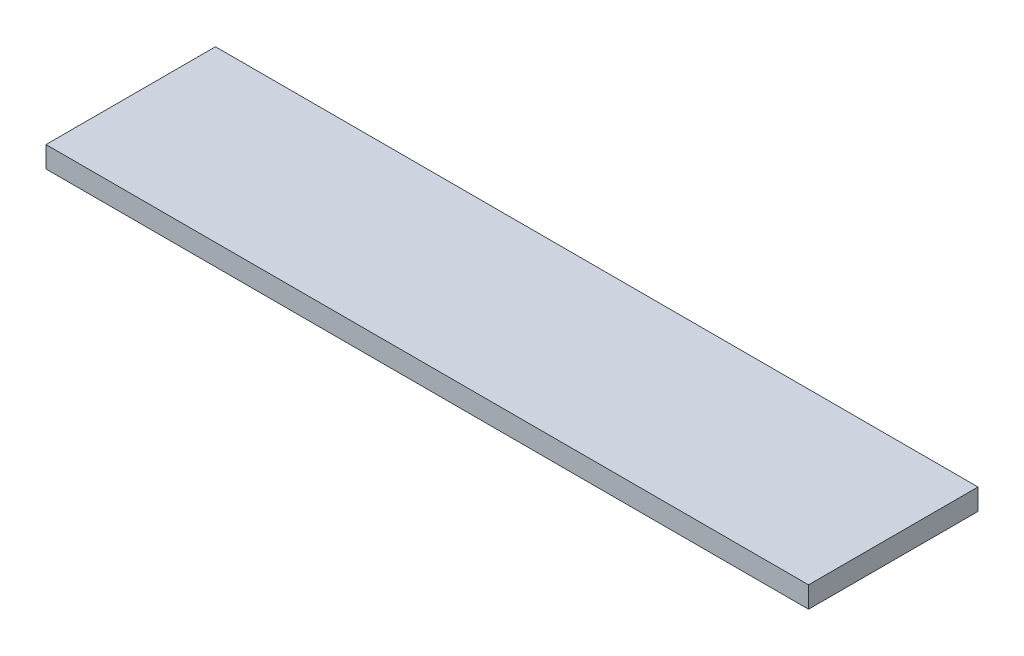
SolidWorks part; units mm, degrees
ref_plane "正面" through (0, 0, 0) normal (0, 0, 1) x (1, 0, 0)
ref_plane "平面" through (0, 0, 0) normal (0, 1, 0) x (1, 0, 0)
ref_plane "右側面" through (0, 0, 0) normal (1, 0, 0) x (0, 0, -1)
sketch "ｽｹｯﾁ1" plane through (0, 0, 0) normal (0, 1, 0) x (1, 0, 0)
  line L1 (-90, 20) -> (90, 20)
  line L2 (-90, 20) -> (-90, -20)
  line L3 (-90, -20) -> (90, -20)
  line L4 (90, 20) -> (90, -20)
  line L5 (-90, 20) -> (90, -20) construction
  line L6 (-90, -20) -> (90, 20) construction
  point P0 (0, 0)
  dimension "D1" = 180
  dimension "D2" = 40
extrude "ﾎﾞｽ - 押し出し1" add sketch "ｽｹｯﾁ1" along normal blind 5
